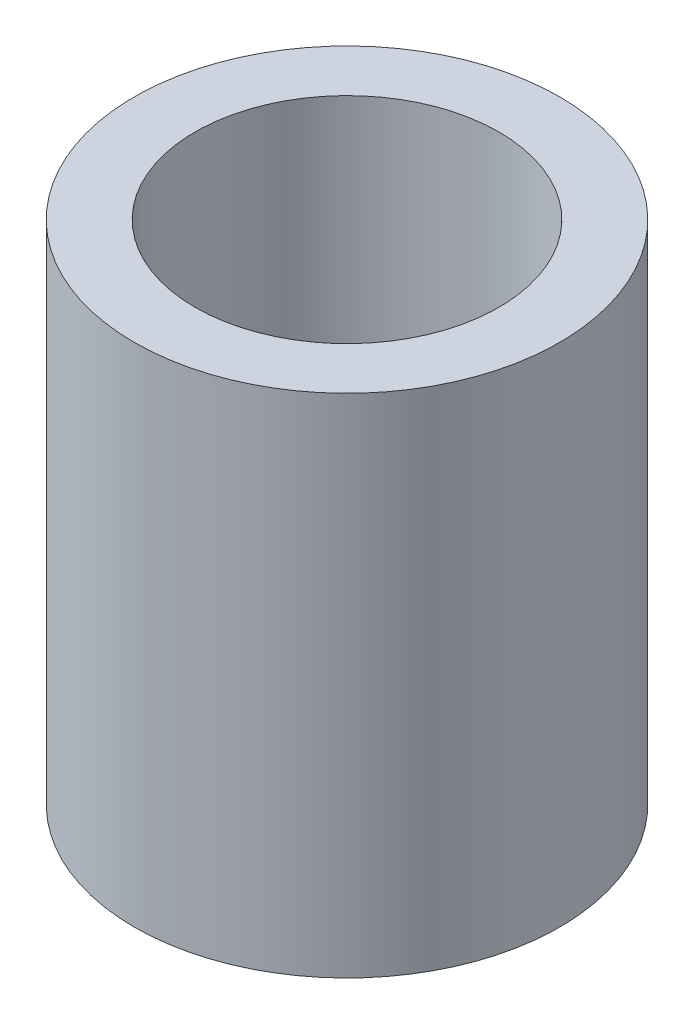
SolidWorks part; units mm, degrees
ref_plane "Front Plane" through (0, 0, 0) normal (0, 0, 1) x (1, 0, 0)
ref_plane "Top Plane" through (0, 0, 0) normal (0, 1, 0) x (1, 0, 0)
ref_plane "Right Plane" through (0, 0, 0) normal (1, 0, 0) x (0, 0, -1)
sketch "Sketch1" plane through (0, 0, 0) normal (0, 1, 0) x (1, 0, 0)
  circle A0 centre (0, 0) radius 2.1
  circle A1 centre (0, 0) radius 1.5
  dimension "D1" = 4.2
  dimension "D2" = 3
extrude "Boss-Extrude1" add sketch "Sketch1" along normal blind 5
